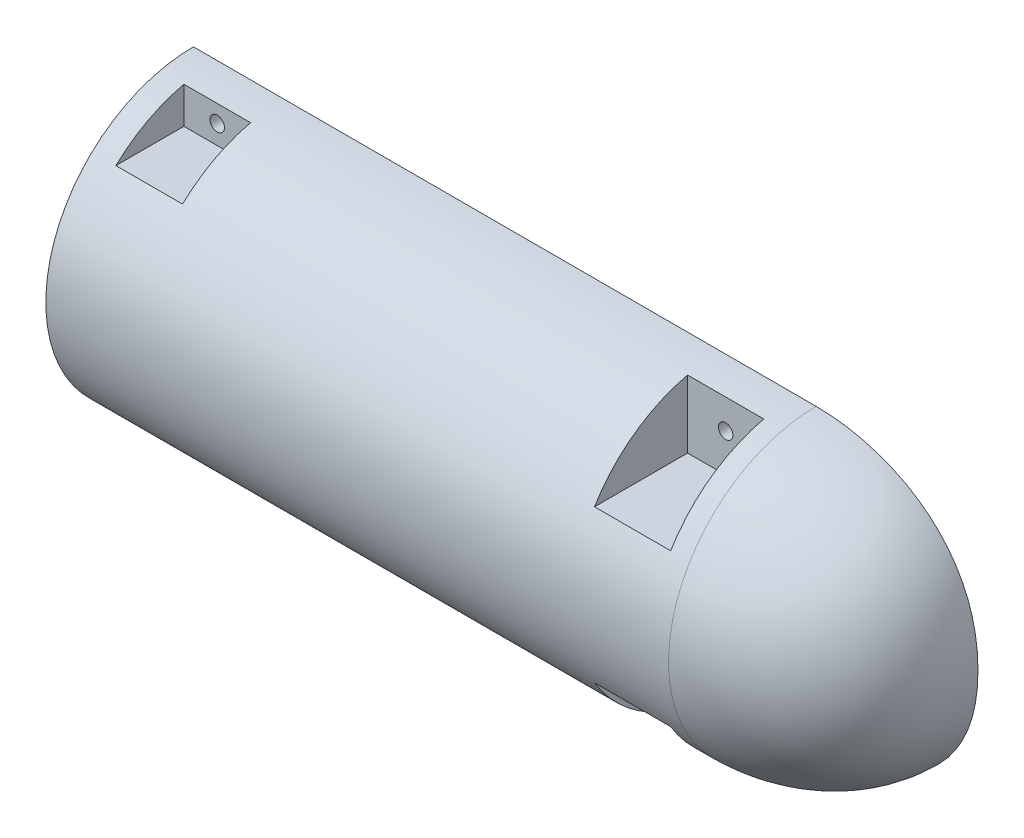
SolidWorks part; units mm, degrees
material "ABS"
ref_plane "Front Plane" through (0, 0, 0) normal (0, 0, 1) x (1, 0, 0)
ref_plane "Top Plane" through (0, 0, 0) normal (0, 1, 0) x (1, 0, 0)
ref_plane "Right Plane" through (0, 0, 0) normal (1, 0, 0) x (0, 0, -1)
sketch "Sketch1" plane through (0, 0, 0) normal (0, 0, 1) x (1, 0, 0)
  line L0 (-52.9373, 0) -> (191.3577, 0) construction
  line L9 (71.5183, 31) -> (136.2706, 31) construction
  line L30 (6.2183, 14) -> (6.2183, 6)
  line L31 (-10.1714, 24.7314) -> (-27.7817, 24.7314)
  line L44 (-56.9817, 31) -> (71.5183, 31)
  line L46 (136.2706, 31) -> (136.2706, 26) construction
  line L47 (136.2706, 26) -> (71.5183, 26) construction
  line L50 (-56.9817, 31) -> (-59.2817, 31)
  line L52 (-59.2817, 31) -> (-59.2817, 24.7314)
  line L54 (71.5183, 13) -> (71.5183, 26) construction
  line L58 (6.2183, 14) -> (71.5183, 14)
  line L78 (71.5183, 14) -> (71.5183, 26)
  line L80 (105.5183, 0) -> (105.5183, 50.2797) construction
  line L81 (100.5183, 0) -> (100.5183, 50.2797) construction
  line L82 (100.5183, 0) -> (105.5183, 0)
  line L83 (3.7183, 24.7314) -> (3.7183, 6)
  line L84 (3.7183, 6) -> (6.2183, 6)
  line L86 (-10.1714, 24.7314) -> (3.7183, 24.7314)
  line L89 (-27.7817, 24.7314) -> (-27.7817, 26.5545)
  line L90 (-27.7817, 26.5545) -> (-35.2817, 26.5545)
  line L91 (-35.2817, 26.5545) -> (-35.2817, 24.7314)
  line L92 (-35.2817, 24.7314) -> (-38.2817, 24.7314)
  line L95 (-38.2817, 21.5343) -> (-38.2817, 24.7314)
  line L96 (-59.2817, 24.7314) -> (-59.2817, 20.4164)
  line L97 (-59.2817, 20.4164) -> (-38.2817, 21.5343)
  spline S0 degree 3 poles (71.5183, 31) (87.3369, 31) (105.5183, 21.7717) (105.5183, 0) knots 0 0 0 0 1 1 1 1
  spline S1 degree 3 poles (71.5183, 26) (84.5012, 26) (100.5183, 18.46) (100.5183, 0) knots 0 0 0 0 1 1 1 1
  dimension "D2" = 5
  dimension "D3" = 0
  dimension "D4" = 6
  dimension "D5" = 0
  dimension "D6" = 34
  dimension "D7" = 7.5
  dimension "D8" = 2.5
  dimension "D9" = 3
  dimension "D10" = 14
revolve "Revolve1" add sketch "Sketch1" angle 180 about L0
ref_plane "Plane4" through (0, 0, 7) normal (0, 0, -1) x (-1, 0, 0)
sketch "Sketch2" plane through (0, 0, 7) normal (0, 0, -1) x (-1, 0, 0)
  line L10 (40.2817, 31) -> (40.2817, 22.5343)
  line L11 (40.2817, 22.5343) -> (54.2817, 22.5343)
  line L12 (54.2817, 22.5343) -> (54.2817, 31)
  line L13 (-51.5183, -31) -> (-51.5183, -16)
  line L15 (-67.5183, -16) -> (-51.5183, -16)
  line L20 (-71.5183, -31) -> (59.2817, -31) construction
  line L21 (-6.2183, -14) -> (-71.5183, -14) construction
  line L23 (40.2817, 31) -> (54.2817, 31)
  line L24 (-67.5183, 16) -> (-67.5183, 31)
  line L37 (-71.5183, 31) -> (59.2817, 31) construction
  line L38 (-67.5183, 31) -> (-51.5183, 31)
  line L39 (-120.0889, 0) -> (106.8977, 0) construction
  line L41 (40.2817, -31) -> (54.2817, -31)
  line L43 (54.2817, -22.5343) -> (54.2817, -31)
  line L44 (40.2817, -22.5343) -> (54.2817, -22.5343)
  line L45 (40.2817, -31) -> (40.2817, -22.5343)
  line L56 (-67.5183, 16) -> (-51.5183, 16)
  line L58 (-67.5183, -31) -> (-51.5183, -31)
  line L59 (-67.5183, -16) -> (-67.5183, -31)
  line L60 (-51.5183, 31) -> (-51.5183, 16)
  line L62 (38.2817, 21.5343) -> (38.2817, 24.7314) construction
  point P23 (-59.5183, -24)
  point P35 (-59.5183, 24)
  dimension "D1" = 1
  dimension "D2" = 16
  dimension "D3" = 2
  dimension "D4" = 14
  dimension "D5" = 16
  dimension "D6" = 8
  dimension "D7" = 2
extrude "Cut-Extrude1" cut sketch "Sketch2" against normal up to next
sketch "Sketch3" plane through (0, 0, 7) normal (0, 0, 1) x (1, 0, 0)
  line L0 (-54.2817, 22.5343) -> (-54.2817, 30.1993) construction
  line L1 (-40.2817, 22.5343) -> (-54.2817, 22.5343) construction
  line L13 (17.05, 0) -> (-17.05, 0) construction
  circle A0 centre (-47.2817, 26.5343) radius 1.525
  circle A4 centre (-47.2817, -26.5343) radius 1.525
  circle A7 centre (59.5183, 24) radius 1.525
  circle A8 centre (59.5183, -24) radius 1.525
  dimension "D1" = 3.05
  dimension "D2" = 7
  dimension "D3" = 3.05
  dimension "D4" = 4
  dimension "D6" = 59.5183
  dimension "D5" = 3.05
  dimension "D7" = 24
  dimension "D8" = 24
  dimension "D9" = 59.5183
extrude "Cut-Extrude2" cut sketch "Sketch3" against normal up to next
ref_plane "Plane5" through (0, -31, 0) normal (0, 1, 0) x (1, 0, 0)
sketch "Sketch5" plane through (0, -31, 0) normal (0, 1, 0) x (1, 0, 0)
  line L3 (4.4419, 0) -> (11.6588, -12.5)
  line L4 (11.6588, -12.5) -> (26.0926, -12.5)
  line L5 (26.0926, -12.5) -> (33.3095, 0)
  line L6 (33.3095, 0) -> (26.0926, 12.5)
  line L7 (26.0926, 12.5) -> (11.6588, 12.5)
  line L8 (11.6588, 12.5) -> (4.4419, 0)
  circle A0 centre (18.8757, 0) radius 12.5 construction
  dimension "D1" = 25
extrude "Cut-Extrude3" cut sketch "Sketch5" along normal blind 10
sketch "Sketch6" plane through (0, -31, 0) normal (0, 1, 0) x (1, 0, 0)
  line L2 (71.5183, -31) -> (71.5183, 0) construction
  circle A0 centre (81.5183, 0) radius 8.5
  dimension "D1" = 17
  dimension "D2" = 10
extrude "Cut-Extrude4" cut sketch "Sketch6" along normal up to next
